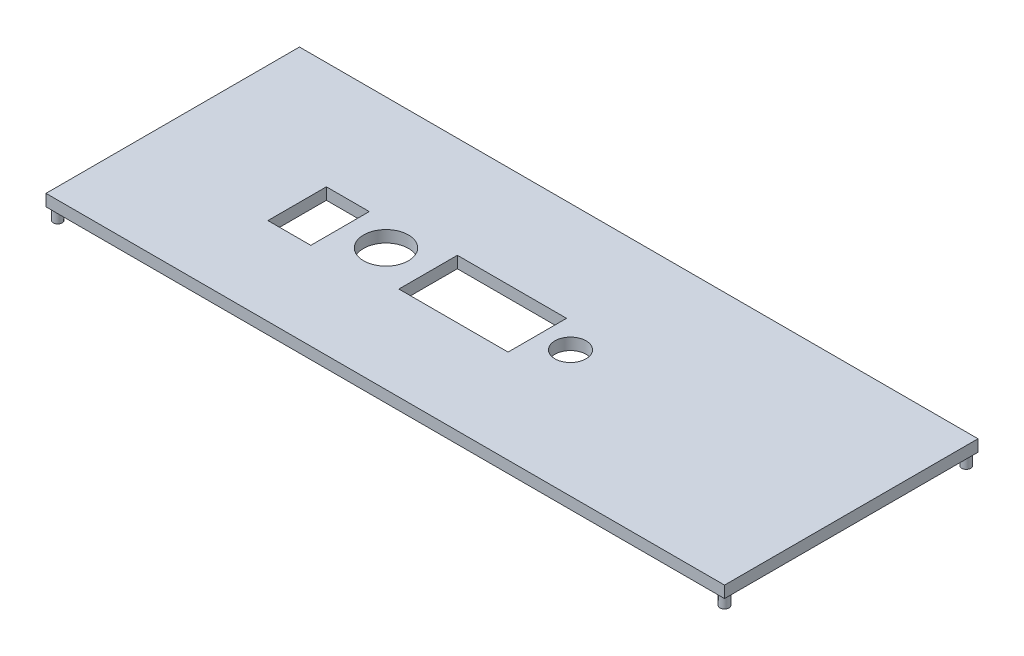
SolidWorks part; units mm, degrees
ref_plane "Front Plane" through (0, 0, 0) normal (0, 0, 1) x (1, 0, 0)
ref_plane "Top Plane" through (0, 0, 0) normal (0, 1, 0) x (1, 0, 0)
ref_plane "Right Plane" through (0, 0, 0) normal (1, 0, 0) x (0, 0, -1)
sketch "Sketch1" plane through (0, 0, 0) normal (0, 1, 0) x (1, 0, 0)
  line L1 (-87, -32.5) -> (87, -32.5)
  line L2 (-87, -32.5) -> (-87, 32.5)
  line L3 (-87, 32.5) -> (87, 32.5)
  line L4 (87, -32.5) -> (87, 32.5)
  line L5 (-87, -32.5) -> (87, 32.5) construction
  line L6 (-87, 32.5) -> (87, -32.5) construction
  point P0 (0, 0)
  dimension "D1" = 65
  dimension "D2" = 174
extrude "Boss-Extrude1" add sketch "Sketch1" along normal blind 3
sketch "Sketch2" plane through (0, 3, 0) normal (0, 1, 0) x (1, 0, 0)
  line L0 (87, 32.5) -> (-87, 32.5) construction
  line L1 (87, -32.5) -> (87, 32.5) construction
  line L3 (-20.5, -8.5096) -> (7.5, -8.5096)
  line L4 (-20.5, -8.5096) -> (-20.5, 6.4904)
  line L5 (-20.5, 6.4904) -> (7.5, 6.4904)
  line L6 (7.5, -8.5096) -> (7.5, 6.4904)
  line L7 (-20.5, -8.5096) -> (7.5, 6.4904) construction
  line L8 (-20.5, 6.4904) -> (7.5, -8.5096) construction
  line L9 (-52.5, 4.904) -> (-41.5, 4.904)
  line L10 (-52.5, 4.904) -> (-52.5, -10.096)
  line L11 (-52.5, -10.096) -> (-41.5, -10.096)
  line L12 (-41.5, 4.904) -> (-41.5, -10.096)
  line L13 (-52.5, 4.904) -> (-41.5, -10.096) construction
  line L14 (-52.5, -10.096) -> (-41.5, 4.904) construction
  circle A0 centre (15, 0) radius 4
  circle A1 centre (-31.3, -1.0096) radius 5.75
  point P6 (-6.5, -1.0096)
  point P13 (-47, -2.596)
  dimension "D1" = 8
  dimension "D7" = 11.5
  dimension "D8" = 118.3
  dimension "D2" = 32.5
  dimension "D3" = 72
  dimension "D4" = 28
  dimension "D5" = 15
  dimension "D6" = 93.5
  dimension "D9" = 11
  dimension "D10" = 15
  dimension "D11" = 134
extrude "Cut-Extrude1" cut sketch "Sketch2" against normal blind 3
sketch "Sketch3" plane through (0, 0, 0) normal (0, -1, 0) x (1, 0, 0)
  line L0 (-87, -32.5) -> (-87, 32.5) construction
  line L1 (-87, 32.5) -> (87, 32.5) construction
  circle A0 centre (-85.5, 31) radius 1.15
  circle A1 centre (85.5, 31) radius 1.15
  circle A2 centre (85.5, -31) radius 1.15
  circle A3 centre (-85.5, -31) radius 1.15
  dimension "D1" = 2.3
  dimension "D2" = 1.5
  dimension "D3" = 1.5
  dimension "D4" = 2
  dimension "D5" = 2
extrude "Boss-Extrude2" add sketch "Sketch3" along normal blind 3
